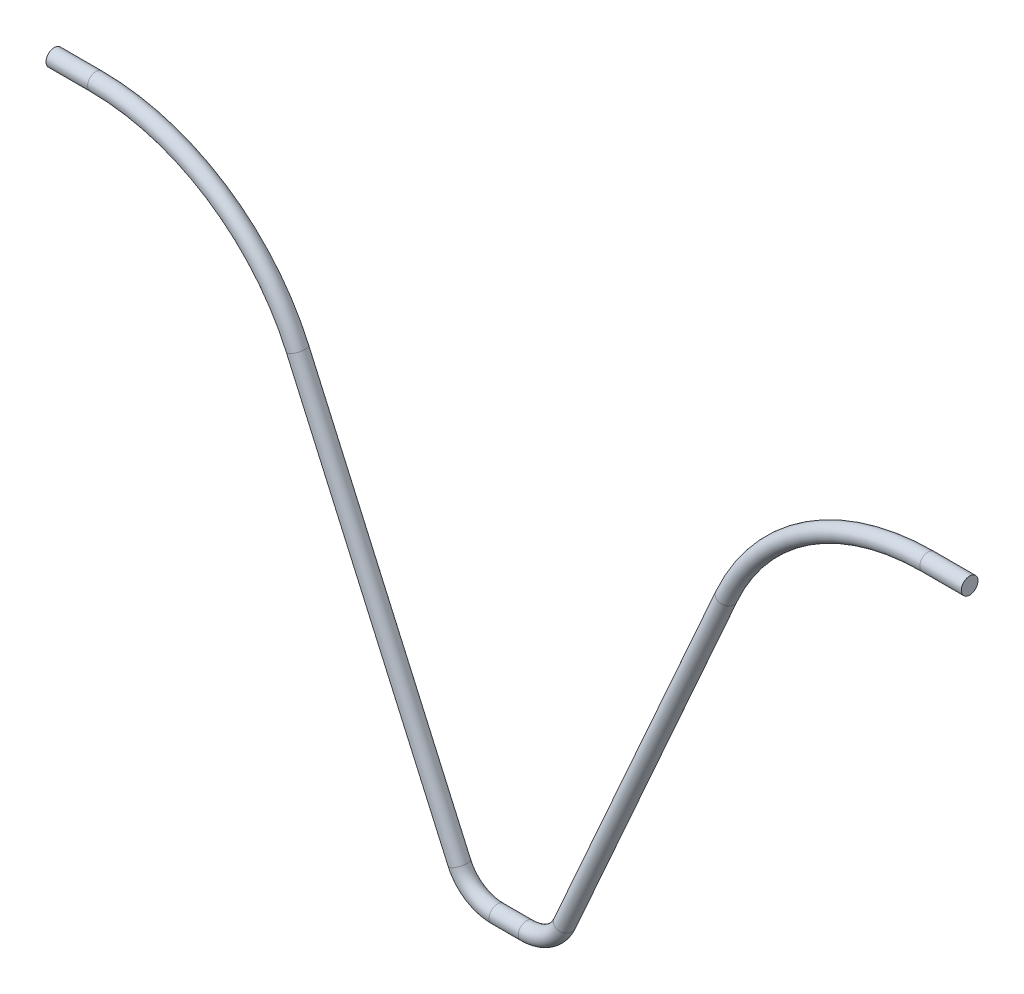
SolidWorks part; units mm, degrees
ref_plane "Front Plane" through (0, 0, 0) normal (0, 0, 1) x (1, 0, 0)
ref_plane "Top Plane" through (0, 0, 0) normal (0, 1, 0) x (1, 0, 0)
ref_plane "Right Plane" through (0, 0, 0) normal (1, 0, 0) x (0, 0, -1)
sketch "Sketch1" plane through (0, 0, 0) normal (0, 0, 1) x (1, 0, 0)
  line L0 (0, 0) -> (0, 50.6373) construction
  line L1 (-3.5, 0) -> (3.5, 0)
  line L2 (12.6388, 5.9402) -> (51.5344, 93.4974)
  line L3 (100, 125) -> (110, 125)
  line L4 (-12.6388, 5.9402) -> (-51.5344, 93.4974)
  line L5 (-100, 125) -> (-110, 125)
  arc A0 (51.5344, 93.4974) -> (100, 125) centre (100, 71.9675) cw
  arc A1 (-51.5344, 93.4974) -> (-100, 125) centre (-100, 71.9675) ccw
  arc A2 (3.5, 0) -> (12.6388, 5.9402) centre (3.5, 10) ccw
  arc A3 (-12.6388, 5.9402) -> (-3.5, 0) centre (-3.5, 10) ccw
  point P15 (10, 0)
  point P18 (-10, 0)
  dimension "D5" = 10
  dimension "D1" = 10
  dimension "D2" = 100
  dimension "D3" = 10
  dimension "D4" = 125
  dimension "D6" = 7
ref_plane "Plane1" through (-110, 0, 0) normal (1, 0, 0) x (0, 0, -1)
sketch "Sketch2" plane through (-110, 0, 0) normal (1, 0, 0) x (0, 0, -1)
  line L0 (0, 125) -> (0, 93.4974) construction
  circle A0 centre (0, 125) radius 2
  point P4 (0, 0)
sweep "Sweep1" add profiles "Sketch2" path "Sketch1"
